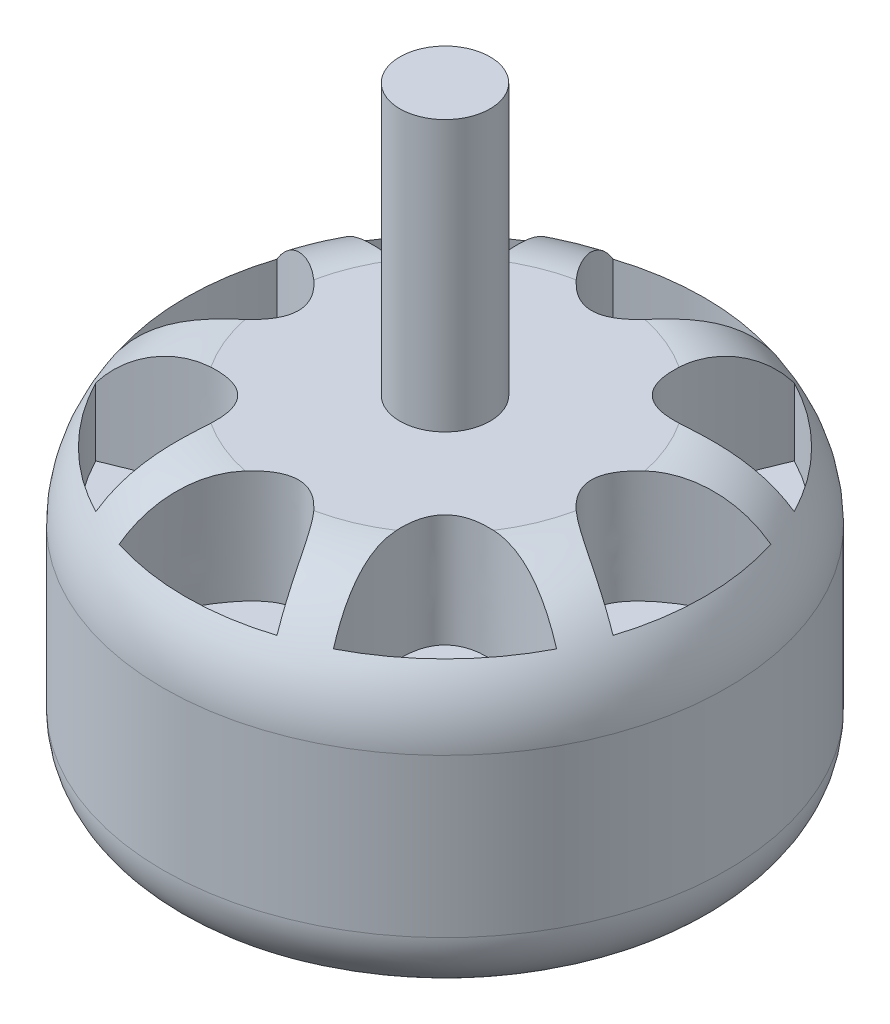
SolidWorks part; units mm, degrees
ref_plane "Front Plane" through (0, 0, 0) normal (0, 0, 1) x (1, 0, 0)
ref_plane "Top Plane" through (0, 0, 0) normal (0, 1, 0) x (1, 0, 0)
ref_plane "Right Plane" through (0, 0, 0) normal (1, 0, 0) x (0, 0, -1)
sketch "Sketch1" plane through (0, 0, 0) normal (0, 1, 0) x (1, 0, 0)
  circle A0 centre (0, 0) radius 12.5
  dimension "D1" = 25
extrude "Boss-Extrude1" add sketch "Sketch1" along normal blind 15
sketch "Sketch2" plane through (0, 15, 0) normal (0, 1, 0) x (1, 0, 0)
  circle A0 centre (0, 0) radius 2
  dimension "D1" = 4
extrude "Boss-Extrude2" add sketch "Sketch2" along normal blind 12
fillet "Fillet1" radius 5 1 edges at (0, 15, 12.5)
fillet "Fillet2" radius 3 1 edges at (0, 0, 12.5)
sketch "Sketch3" plane through (0, 15, 0) normal (0, 1, 0) x (1, 0, 0)
  line L0 (0, 0) -> (0, -50000) construction
  circle A1 centre (0, 0) radius 12.5 construction
  circle A2 centre (0, 0) radius 11.5
  arc A3 (3.5, 10.9545) -> (-3.5, 10.9545) centre (0, 0) ccw
  arc A4 (10.2208, 5.2711) -> (5.2711, 10.2208) centre (0, 0) ccw
  arc A5 (10.9545, -3.5) -> (10.9545, 3.5) centre (0, 0) ccw
  arc A6 (5.2711, -10.2208) -> (10.2208, -5.2711) centre (0, 0) ccw
  arc A7 (-3.5, -10.9545) -> (3.5, -10.9545) centre (0, 0) ccw
  arc A8 (-10.2208, -5.2711) -> (-5.2711, -10.2208) centre (0, 0) ccw
  arc A9 (-10.9545, 3.5) -> (-10.9545, -3.5) centre (0, 0) ccw
  arc A10 (-5.2711, 10.2208) -> (-10.2208, 5.2711) centre (0, 0) ccw
  spline S0 degree 2 poles (-3.5, 10.9545) (0, 2.0455) (3.5, 10.9545) knots 0 0 0 1 1 1
  spline S1 degree 2 poles (5.2711, 10.2208) (1.4464, 1.4464) (10.2208, 5.2711) knots 0 0 0 1 1 1
  spline S2 degree 2 poles (10.9545, 3.5) (2.0455, 0) (10.9545, -3.5) knots 0 0 0 1 1 1
  spline S3 degree 2 poles (10.2208, -5.2711) (1.4464, -1.4464) (5.2711, -10.2208) knots 0 0 0 1 1 1
  spline S4 degree 2 poles (3.5, -10.9545) (0, -2.0455) (-3.5, -10.9545) knots 0 0 0 1 1 1
  spline S5 degree 2 poles (-5.2711, -10.2208) (-1.4464, -1.4464) (-10.2208, -5.2711) knots 0 0 0 1 1 1
  spline S6 degree 2 poles (-10.9545, -3.5) (-2.0455, 0) (-10.9545, 3.5) knots 0 0 0 1 1 1
  spline S7 degree 2 poles (-10.2208, 5.2711) (-1.4464, 1.4464) (-5.2711, 10.2208) knots 0 0 0 1 1 1
  point P6 (0, 12.5)
  point P35 (0, 0)
  dimension "D2" = 6
  dimension "D3" = 7
  dimension "D1" = 1
  dimension "D4" = 8
extrude "Cut-Extrude1" cut sketch "Sketch3" against normal blind 5
